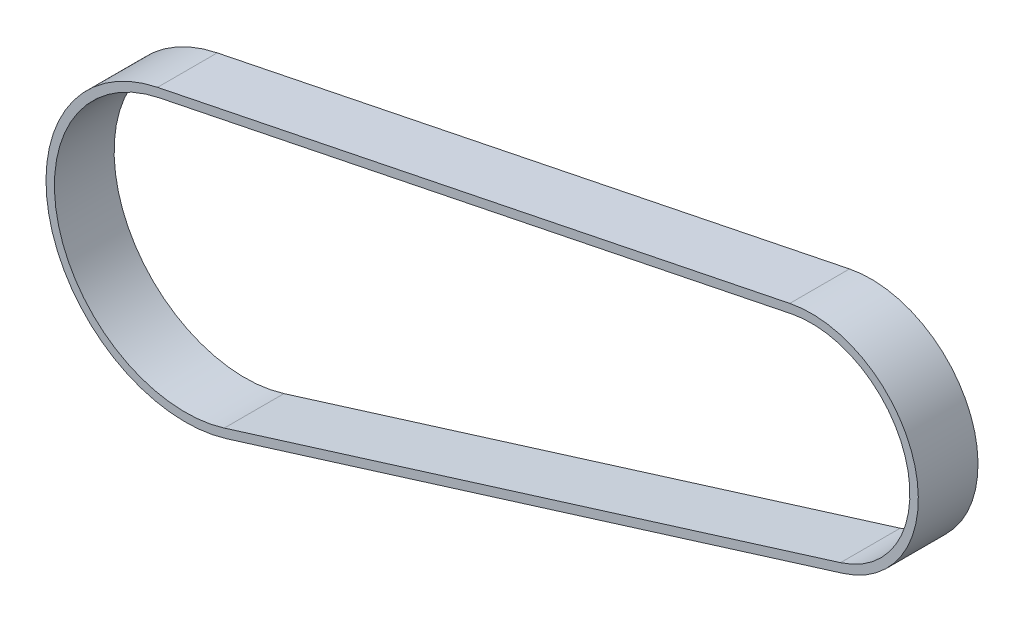
SolidWorks part; units mm, degrees
material "POLYURETHANE (11671)"
ref_plane "Front Plane" through (0, 0, 0) normal (0, 0, 1) x (1, 0, 0)
ref_plane "Top Plane" through (0, 0, 0) normal (0, 1, 0) x (1, 0, 0)
ref_plane "Right Plane" through (0, 0, 0) normal (1, 0, 0) x (0, 0, -1)
sketch "Sketch2" plane through (0, 0, 0) normal (0, 0, 1) x (1, 0, 0)
  line L0 (0, 0) -> (1, 0) construction
  line L1 (0, 0) -> (0, 1) construction
  line L2 (6.4519, 32.1659) -> (101.7749, 51.616)
  line L3 (109.1653, 22.8319) -> (16.2627, -6.0453)
  arc A0 (16.2627, -6.0453) -> (6.4519, 32.1659) centre (10.4005, 12.8146) cw
  arc A1 (101.7749, 51.616) -> (109.1653, 22.8319) centre (104.7493, 37.0389) cw
extrude "Extrude-Thin1" add sketch "Sketch2" along normal blind 9 thin thin type one direction wall 1.27
